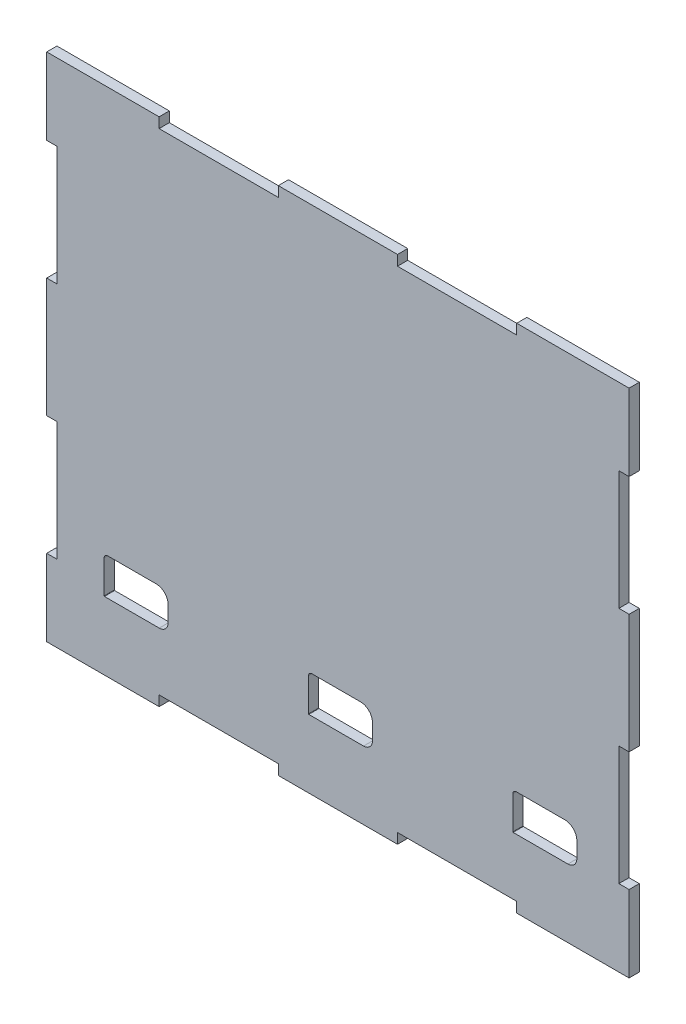
SolidWorks part; units mm, degrees
ref_plane "Front Plane" through (0, 0, 0) normal (0, 0, 1) x (1, 0, 0)
ref_plane "Top Plane" through (0, 0, 0) normal (0, 1, 0) x (1, 0, 0)
ref_plane "Right Plane" through (0, 0, 0) normal (1, 0, 0) x (0, 0, -1)
sketch "Model" plane through (0, 0, 0) normal (0, 0, 1) x (1, 0, 0)
  line L0 (85.5, 75) -> (82.5, 75)
  line L1 (82.5, 75) -> (52.5, 75)
  line L2 (52.5, 75) -> (52.5, 72)
  line L3 (52.5, 72) -> (17.5, 72)
  line L4 (17.5, 72) -> (17.5, 75)
  line L5 (17.5, 75) -> (-17.5, 75)
  line L6 (-17.5, 75) -> (-17.5, 72)
  line L7 (-17.5, 72) -> (-52.5, 72)
  line L8 (-52.5, 72) -> (-52.5, 75)
  line L9 (-52.5, 75) -> (-82.5, 75)
  line L10 (-82.5, 75) -> (-85.5, 75)
  line L11 (-85.5, 75) -> (-85.5, 72)
  line L12 (-85.5, 72) -> (-85.5, 52.5)
  line L13 (-85.5, 52.5) -> (-82.5, 52.5)
  line L14 (-82.5, 52.5) -> (-82.5, 17.5)
  line L15 (-82.5, 17.5) -> (-85.5, 17.5)
  line L16 (-85.5, 17.5) -> (-85.5, -17.5)
  line L17 (-85.5, -17.5) -> (-82.5, -17.5)
  line L18 (-82.5, -17.5) -> (-82.5, -52.5)
  line L19 (-82.5, -52.5) -> (-85.5, -52.5)
  line L20 (-85.5, -52.5) -> (-85.5, -72)
  line L21 (-85.5, -72) -> (-85.5, -75)
  line L22 (-85.5, -75) -> (-82.5, -75)
  line L23 (-82.5, -75) -> (-52.5, -75)
  line L24 (-52.5, -75) -> (-52.5, -72)
  line L25 (-52.5, -72) -> (-17.5, -72)
  line L26 (-17.5, -72) -> (-17.5, -75)
  line L27 (-17.5, -75) -> (17.5, -75)
  line L28 (17.5, -75) -> (17.5, -72)
  line L29 (17.5, -72) -> (52.5, -72)
  line L30 (52.5, -72) -> (52.5, -75)
  line L31 (52.5, -75) -> (82.5, -75)
  line L32 (82.5, -75) -> (85.5, -75)
  line L33 (85.5, -75) -> (85.5, -72)
  line L34 (85.5, -72) -> (85.5, -52.5)
  line L35 (85.5, -52.5) -> (82.5, -52.5)
  line L36 (82.5, -52.5) -> (82.5, -17.5)
  line L37 (82.5, -17.5) -> (85.5, -17.5)
  line L38 (85.5, -17.5) -> (85.5, 17.5)
  line L39 (85.5, 17.5) -> (82.5, 17.5)
  line L40 (82.5, 17.5) -> (82.5, 52.5)
  line L41 (82.5, 52.5) -> (85.5, 52.5)
  line L42 (85.5, 52.5) -> (85.5, 72)
  line L43 (85.5, 72) -> (85.5, 75)
extrude "Boss-Extrude1" add sketch "Model" along normal blind 3
sketch "Sketch1" plane through (0, 0, 3) normal (0, 0, 1) x (1, 0, 0)
  line L0 (-52.4625, -55) -> (-68.5375, -55)
  line L1 (-67.6375, -44.2) -> (-53.3625, -44.2)
  line L2 (-68.6375, -54.9) -> (-68.6375, -45.2)
  line L3 (-49.8375, -52.375) -> (-49.8375, -47.725)
  line L4 (-60.5, -55) -> (-60.5, -75) construction
  line L5 (7.5375, -55) -> (-8.5375, -55)
  line L6 (-7.6375, -44.2) -> (6.6375, -44.2)
  line L7 (-8.6375, -54.9) -> (-8.6375, -45.2)
  line L8 (10.1625, -52.375) -> (10.1625, -47.725)
  line L9 (67.5375, -55) -> (51.4625, -55)
  line L10 (52.3625, -44.2) -> (66.6375, -44.2)
  line L11 (51.3625, -54.9) -> (51.3625, -45.2)
  line L12 (70.1625, -52.375) -> (70.1625, -47.725)
  line L13 (-85.5, -75) -> (-60.5, -75) construction
  line L14 (-85.5, -75) -> (-52.5, -75) construction
  arc A0 (-49.8375, -52.375) -> (-52.4625, -55) centre (-52.4625, -52.375) cw
  arc A1 (-49.8375, -47.725) -> (-53.3625, -44.2) centre (-53.3625, -47.725) ccw
  arc A2 (-68.5375, -55) -> (-68.6375, -54.9) centre (-68.5375, -54.9) cw
  arc A3 (-68.6375, -45.2) -> (-67.6375, -44.2) centre (-67.6375, -45.2) cw
  arc A4 (10.1625, -52.375) -> (7.5375, -55) centre (7.5375, -52.375) cw
  arc A5 (10.1625, -47.725) -> (6.6375, -44.2) centre (6.6375, -47.725) ccw
  arc A6 (-8.5375, -55) -> (-8.6375, -54.9) centre (-8.5375, -54.9) cw
  arc A7 (-8.6375, -45.2) -> (-7.6375, -44.2) centre (-7.6375, -45.2) cw
  arc A8 (70.1625, -52.375) -> (67.5375, -55) centre (67.5375, -52.375) cw
  arc A9 (70.1625, -47.725) -> (66.6375, -44.2) centre (66.6375, -47.725) ccw
  arc A10 (51.4625, -55) -> (51.3625, -54.9) centre (51.4625, -54.9) cw
  arc A11 (51.3625, -45.2) -> (52.3625, -44.2) centre (52.3625, -45.2) cw
  dimension "D1" = 20
  dimension "D2" = 25
extrude "Cut-Extrude1" cut sketch "Sketch1" against normal through all
